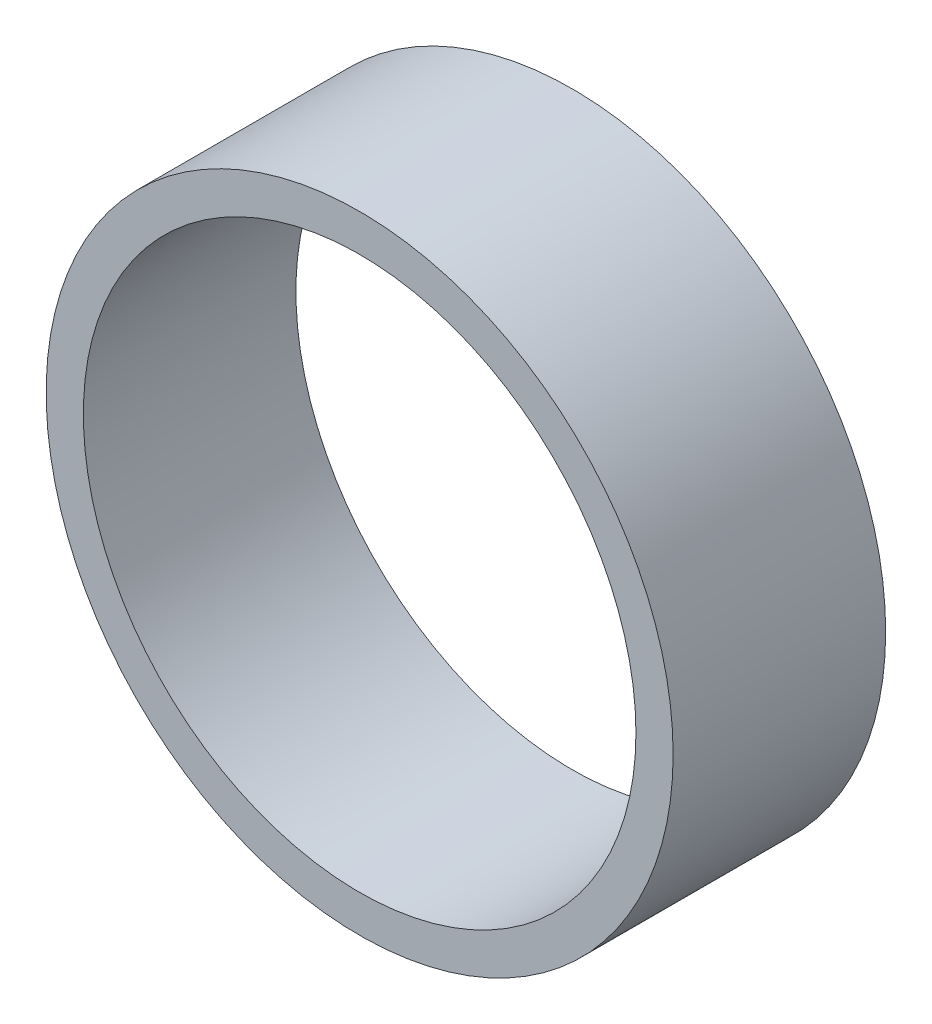
SolidWorks part; units mm, degrees
ref_plane "前视基准面" through (0, 0, 0) normal (0, 0, 1) x (1, 0, 0)
ref_plane "上视基准面" through (0, 0, 0) normal (0, 1, 0) x (1, 0, 0)
ref_plane "右视基准面" through (0, 0, 0) normal (1, 0, 0) x (0, 0, -1)
other "Configuration Table"
sketch "草图1" plane through (0, 0, 0) normal (0, 0, 1) x (1, 0, 0)
  circle A0 centre (0, 0) radius 14.75
  circle A1 centre (0, 0) radius 13
  dimension "D1" = 29.5
  dimension "D2" = 26
extrude "凸台-拉伸1" add sketch "草图1" along normal blind 10
